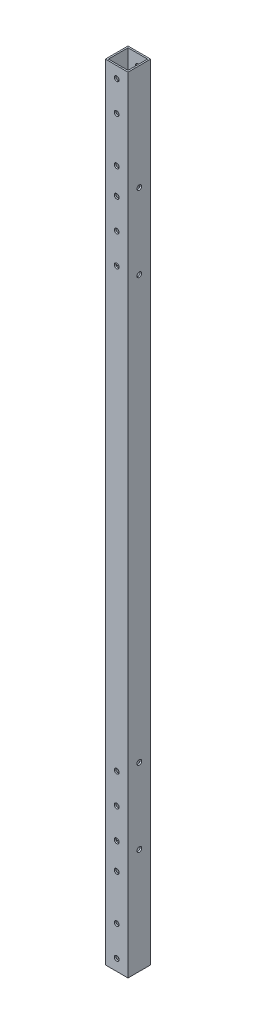
SolidWorks part; units mm, degrees
ref_plane "前视基准面" through (0, 0, 0) normal (0, 0, 1) x (1, 0, 0)
ref_plane "上视基准面" through (0, 0, 0) normal (0, 1, 0) x (1, 0, 0)
ref_plane "右视基准面" through (0, 0, 0) normal (1, 0, 0) x (0, 0, -1)
sketch "草图1" plane through (0, 0, 0) normal (0, 1, 0) x (1, 0, 0)
  line L1 (-7.5, -7.5) -> (7.5, -7.5)
  line L2 (-7.5, -7.5) -> (-7.5, 7.5)
  line L3 (-7.5, 7.5) -> (7.5, 7.5)
  line L4 (7.5, -7.5) -> (7.5, 7.5)
  line L5 (-7.5, -7.5) -> (7.5, 7.5) construction
  line L6 (-7.5, 7.5) -> (7.5, -7.5) construction
  point P0 (0, 0)
  dimension "D1" = 15
  dimension "D2" = 15
extrude "拉伸-薄壁1" add sketch "草图1" along normal blind 520 thin thin type one direction reverse wall 1
sketch "草图2" plane through (0, 0, 7.5) normal (0, 0, 1) x (1, 0, 0)
  line L0 (0, 0) -> (0, 520) construction
  line L1 (-7.5, 520) -> (7.5, 520) construction
  line L2 (-1000, 260) -> (49000, 260) construction
  line L3 (-7.5, 0) -> (7.5, 0) construction
  circle A0 centre (0, 7.5) radius 1.6
  circle A1 centre (0, 27.5) radius 1.6
  circle A2 centre (0, 57.5) radius 1.6
  circle A3 centre (0, 75) radius 1.6
  circle A4 centre (0, 95) radius 1.6
  circle A5 centre (0, 115) radius 1.6
  circle A6 centre (0, 405) radius 1.6
  circle A7 centre (0, 425) radius 1.6
  circle A8 centre (0, 445) radius 1.6
  circle A9 centre (0, 462.5) radius 1.6
  circle A10 centre (0, 492.5) radius 1.6
  circle A11 centre (0, 512.5) radius 1.6
  point P8 (0, 260)
  dimension "D1" = 3.2
  dimension "D2" = 7.5
  dimension "D3" = 20
  dimension "D4" = 30
  dimension "D5" = 20
  dimension "D6" = 20
  dimension "D7" = 165
extrude "切除-拉伸1" cut sketch "草图2" against normal through all
sketch "草图3" plane through (7.5, 0, 0) normal (1, 0, 0) x (0, 0, -1)
  line L0 (0, 0) -> (0, 520) construction
  line L1 (-7.5, 520) -> (7.5, 520) construction
  line L2 (-1000, 260) -> (49000, 260) construction
  circle A0 centre (0, 70) radius 1.6
  circle A1 centre (0, 120) radius 1.6
  circle A2 centre (0, 400) radius 1.6
  circle A3 centre (0, 450) radius 1.6
  point P12 (0, 260)
  dimension "D1" = 3.2
  dimension "D2" = 190
  dimension "D3" = 50
extrude "切除-拉伸2" cut sketch "草图3" against normal through all
